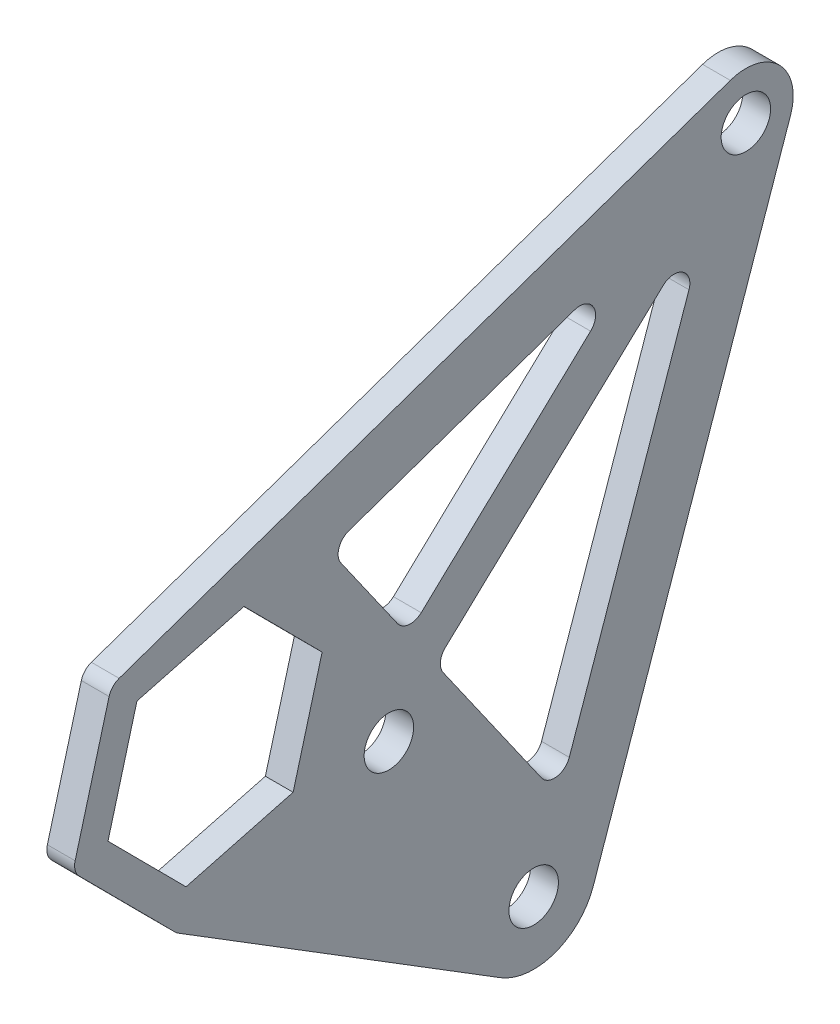
SolidWorks part; units mm, degrees
material "Ti-6Al-2Sn-2Zr-2Mo-2Cr-0.25Si (SS)"
ref_plane "Front Plane" through (0, 0, 0) normal (0, 0, 1) x (1, 0, 0)
ref_plane "Top Plane" through (0, 0, 0) normal (0, 1, 0) x (1, 0, 0)
ref_plane "Right Plane" through (0, 0, 0) normal (1, 0, 0) x (0, 0, -1)
other "Bounding Box"
ref_plane "Default Plane" through (0, 2.286, 19.05) normal (0, -1, 0) x (-1, 0, 0)
sketch "Sketch1" plane through (0, 0, 0) normal (1, 0, 0) x (0, 0, -1)
  line L0 (-35.921, -35.921) -> (0, 0) construction
  line L1 (-35.921, -35.921) -> (-21.3522, -56.7275) construction
  line L2 (0, 0) -> (29.816, 0) construction
  line L3 (-15.3527, -58.808) -> (4.4996, -1.5604)
  line L4 (-3.2607, 3.4712) -> (-40.2686, -31.2928)
  line L5 (-41.1226, -39.5632) -> (-26.5538, -60.3697)
  circle A0 centre (0, 0) radius 2.4892
  arc A1 (4.4996, -1.5604) -> (-3.2607, 3.4712) centre (0, 0) ccw
  circle A2 centre (-35.921, -35.921) radius 2.4892
  circle A3 centre (-21.3522, -56.7275) radius 2.4892
  arc A4 (-40.2686, -31.2928) -> (-41.1226, -39.5632) centre (-35.921, -35.921) ccw
  arc A5 (-26.5538, -60.3697) -> (-15.3527, -58.808) centre (-21.3522, -56.7275) ccw
  dimension "D1" = 4.9784
  dimension "D2" = 50.8
  dimension "D6" = 12.7
  dimension "D7" = 4.7625
  dimension "D3" = 25.4
  dimension "D4" = 45
  dimension "D5" = 100
extrude "Boss-Extrude1" add sketch "Sketch1" along normal blind 2.794
sketch "Sketch2" plane through (2.794, 0, 0) normal (1, 0, 0) x (0, 0, -1)
  line L0 (-3.6123, -5.5713) -> (-31.2449, -31.5284)
  line L1 (-31.2449, -31.5284) -> (-18.7846, -49.3235)
  line L2 (-18.7846, -49.3235) -> (-3.6123, -5.5713)
  line L3 (-15.3527, -58.808) -> (4.4996, -1.5604) construction
  line L4 (-3.2607, 3.4712) -> (-40.2686, -31.2928) construction
  line L5 (-41.1226, -39.5632) -> (-26.5538, -60.3697) construction
  dimension "D1" = 12.7
  dimension "D2" = 6.35
  dimension "D3" = 6.35
extrude "Cut-Extrude1" cut sketch "Sketch2" against normal through all
sketch "Sketch3" plane through (2.794, 0, 0) normal (1, 0, 0) x (0, 0, -1)
  line L0 (-1.5621, 4.499) -> (-63.854, -17.1296)
  line L1 (-56.3284, -38.3906) -> (-45.5545, -35.538)
  line L2 (-45.5545, -35.538) -> (-42.638, -24.7812)
  line L3 (-42.638, -24.7812) -> (-50.4954, -16.877)
  line L4 (-50.4954, -16.877) -> (-61.2693, -19.7296)
  line L5 (-61.2693, -19.7296) -> (-64.1858, -30.4864)
  line L6 (-64.1858, -30.4864) -> (-56.3284, -38.3906)
  line L7 (-63.854, -17.1296) -> (-67.7299, -31.4248)
  line L9 (-45.5545, -35.538) -> (-63.854, -17.1296) construction
  line L10 (-42.638, -24.7812) -> (-67.7299, -31.4248) construction
  line L11 (-3.2607, 3.4712) -> (-40.2686, -31.2928) construction
  line L12 (-41.1226, -39.5632) -> (-26.5538, -60.3697) construction
  line L13 (-3.2607, 3.4712) -> (-40.2686, -31.2928)
  line L14 (-41.1226, -39.5632) -> (-26.5538, -60.3697)
  line L15 (-31.2449, -31.5284) -> (-18.7846, -49.3235) construction
  line L16 (-67.7299, -31.4248) -> (-57.2878, -41.929)
  line L17 (-57.2878, -41.929) -> (-24.697, -62.1251)
  line L18 (-50.4954, -16.877) -> (-57.2878, -41.929) construction
  line L19 (-35.921, -35.921) -> (-66.6872, -27.5793) construction
  line L20 (-53.4119, -27.6338) -> (-35.921, -35.921) construction
  circle A0 centre (-53.4119, -27.6338) radius 9.652 construction
  circle A1 centre (-35.921, -35.921) radius 2.4892 construction
  circle A2 centre (-35.921, -35.921) radius 2.4892 construction
  arc A3 (-26.5538, -60.3697) -> (-15.3527, -58.808) centre (-21.3522, -56.7275) ccw construction
  arc A5 (4.4996, -1.5604) -> (-3.2607, 3.4712) centre (0, 0) ccw construction
  arc A6 (-40.2686, -31.2928) -> (-41.1226, -39.5632) centre (-35.921, -35.921) ccw construction
  arc A7 (-1.5621, 4.499) -> (-3.2607, 3.4712) centre (0, 0) ccw
  arc A8 (-40.2686, -31.2928) -> (-41.1226, -39.5632) centre (-35.921, -35.921) ccw
  arc A9 (-26.5538, -60.3697) -> (-24.697, -62.1251) centre (-21.3522, -56.7275) ccw
  circle A10 centre (-53.4119, -27.6338) radius 3.5643 construction
  dimension "D3" = 19.304
  dimension "D1" = 19.05
  dimension "D2" = 19.3548
  dimension "D4" = 3.175
  dimension "D5" = 50.17
extrude "Boss-Extrude2" add sketch "Sketch3" against normal up to surface (2.794 mm away) up to face at (0, -28.8077, 17.8806)
sketch "Sketch4" plane through (2.794, 0, 0) normal (1, 0, 0) x (0, 0, -1)
  line L0 (-41.9465, -16.2449) -> (-34.0048, -27.5868)
  line L1 (-34.0048, -27.5868) -> (-10.1943, -5.2201)
  line L2 (-10.1943, -5.2201) -> (-41.9465, -16.2449)
  line L3 (-1.5621, 4.499) -> (-63.854, -17.1296) construction
  line L4 (-3.6123, -5.5713) -> (-31.2449, -31.5284) construction
  line L5 (-31.2449, -31.5284) -> (-18.7846, -49.3235) construction
  dimension "D1" = 6.35
  dimension "D2" = 4.7625
extrude "Cut-Extrude2" cut sketch "Sketch4" against normal through all
fillet "Fillet1" radius 1.5875 3 edges at (1.397, -49.3235, 18.7846) (1.397, -5.5713, 3.6123) (1.397, -31.5284, 31.2449)
fillet "Fillet2" radius 1.5875 6 edges at (1.397, -17.1296, 63.854) (1.397, -31.4248, 67.7299) (1.397, -41.929, 57.2878) (1.397, -27.5868, 34.0048) (1.397, -5.2201, 10.1943) (1.397, -16.2449, 41.9465)
equation "\"Unit Measure\"= \"BoundingVolume\" / \"Thickness\"'in^2"
